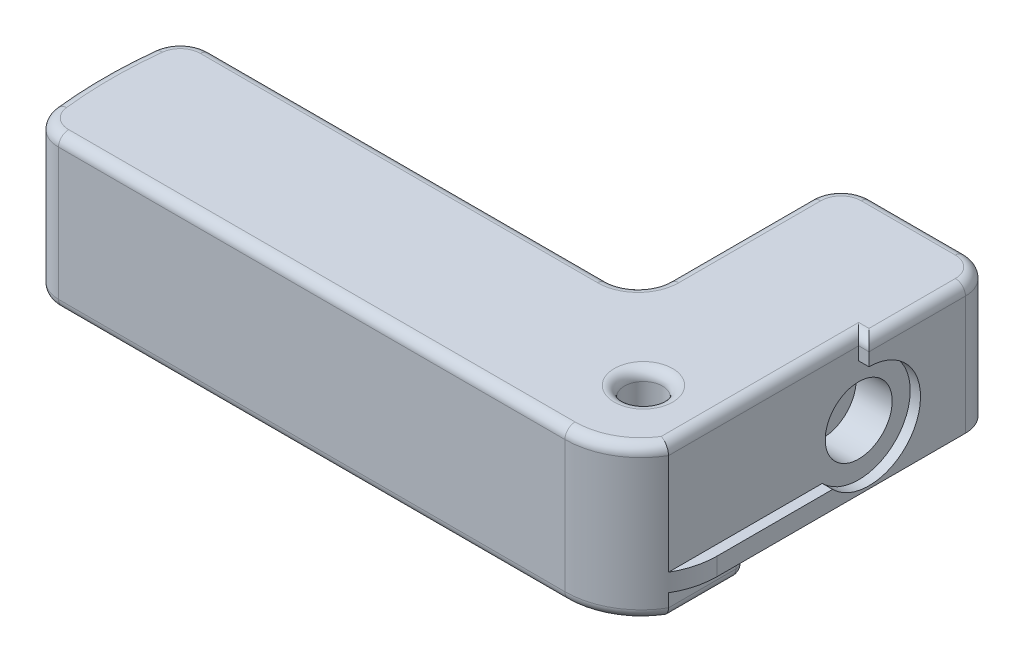
SolidWorks part; units mm, degrees
ref_plane "Front Plane" through (0, 0, 0) normal (0, 0, 1) x (1, 0, 0)
ref_plane "Top Plane" through (0, 0, 0) normal (0, 1, 0) x (1, 0, 0)
ref_plane "Right Plane" through (0, 0, 0) normal (1, 0, 0) x (0, 0, -1)
sketch "Sketch1" plane through (0, 0, 0) normal (0, 1, 0) x (1, 0, 0)
  line L0 (-60.8, 0) -> (0, 0)
  line L1 (0, 0) -> (0, 35)
  line L2 (0, 35) -> (-16.0369, 35)
  line L3 (-16.0369, 35) -> (-16.0369, 15)
  line L4 (-16.0369, 15) -> (-60.8, 15)
  line L6 (-16.0369, 15) -> (0, 0) construction
  circle A0 centre (-8.0184, 7.5) radius 1.875
  arc A1 (-60.8, 15) -> (-60.8, 0) centre (-18.0184, 7.5) ccw
  dimension "D3" = 3.75
  dimension "D5" = 60.8
  dimension "D6" = 43.434
  dimension "D1" = 35
  dimension "D2" = 15
  dimension "D4" = 16.0369
extrude "Boss-Extrude1" add sketch "Sketch1" along normal blind 15
sketch "Sketch2" plane through (0, 0, 0) normal (1, 0, 0) x (0, 0, -1)
  line L0 (22.486, 12.716) -> (22.486, 15)
  line L1 (35, 15) -> (35, 0) construction
  line L2 (0, 15) -> (35, 15) construction
  line L3 (5.625, 15) -> (9.375, 15) construction
  line L4 (0, 15) -> (0, 4.0439)
  line L5 (0, 4.0439) -> (18.8939, 4.0439)
  line L6 (22.486, 7.636) -> (18.8939, 4.0439) construction
  line L8 (0, 0) -> (35, 0) construction
  line L9 (0, 15) -> (0, 0) construction
  line L10 (0, 15) -> (22.486, 15)
  line L11 (0, 0) -> (35, 0)
  line L12 (0, 0) -> (0, 2.286)
  line L13 (0, 2.286) -> (35, 2.286)
  line L14 (35, 0) -> (35, 2.286)
  arc A0 (22.486, 12.716) -> (18.8939, 4.0439) centre (22.486, 7.636) cw
  point P3 (22.486, 2.556)
  point P22 (7.5, 15)
  dimension "D1" = 5.08
  dimension "D2" = 14.986
  dimension "D3" = 12.716
  dimension "D4" = 45
  dimension "D5" = 2.286
extrude "Cut-Extrude1" cut sketch "Sketch2" against normal blind 1.778
sketch "Sketch7" plane through (-1.778, 0, 0) normal (1, 0, 0) x (0, 0, -1)
  line L0 (0, 0) -> (35, 0) construction
  line L1 (11.375, 0) -> (35, 0)
  line L2 (11.375, 0) -> (11.375, 2.286)
  line L3 (11.375, 2.286) -> (35, 2.286)
  line L4 (35, 0) -> (35, 2.286)
  line L6 (9.375, 0) -> (9.375, 15) construction
  dimension "D1" = 2
extrude "Cut-Extrude6" cut sketch "Sketch7" against normal blind 5
sketch "Sketch3" plane through (-1.778, 0, 0) normal (1, 0, 0) x (0, 0, -1)
  circle A0 centre (22.486, 7.636) radius 3.302
  dimension "D1" = 6.604
extrude "Cut-Extrude2" cut sketch "Sketch3" against normal blind 3.556
sketch "Sketch4" plane through (0, 0, -15) normal (0, 0, -1) x (-1, 0, 0)
  line L0 (43.5784, 15) -> (43.5784, 0) construction
  line L1 (16.0369, 15) -> (60.8, 15) construction
  line L2 (16.0369, 0) -> (60.8, 0) construction
  line L4 (6.1434, 15) -> (9.8934, 15) construction
  circle A0 centre (43.5784, 7.5) radius 3.302
  point P12 (8.0184, 15)
  dimension "D1" = 6.604
  dimension "D2" = 35.56
extrude "Cut-Extrude3" cut sketch "Sketch4" against normal blind 3.302
sketch "Sketch5" plane through (0, 0, 0) normal (1, 0, 0) x (0, 0, -1)
  line L1 (35, 0) -> (0, 0)
  line L2 (35, 0) -> (35, 15)
  line L3 (35, 15) -> (0, 15)
  line L4 (0, 0) -> (0, 15)
extrude "Cut-Extrude4" cut sketch "Sketch5" against normal blind 0.762
sketch "Sketch6" plane through (0, 15, 0) normal (0, 1, 0) x (1, 0, 0)
  line L0 (-0.762, 18.8939) -> (-0.762, 0) construction
  line L1 (-60.8, 0) -> (-1.778, 0) construction
  line L2 (-8.262, 0) -> (-0.762, 0)
  line L3 (-0.762, 0) -> (-0.762, 7.5)
  arc A0 (-0.762, 7.5) -> (-8.262, 0) centre (-8.262, 7.5) cw
  dimension "D1" = 7.5
extrude "Cut-Extrude5" cut sketch "Sketch6" against normal through all
fillet "Fillet1" radius 3 5 edges at (-16.0369, 7.5, -15) (-0.762, 8.643, -35) (-16.0369, 7.5, -35) (-60.8, 7.5, 0) (-60.8, 7.5, -15)
fillet "Fillet2" radius 1 30 edges at (-8.0184, 0, -5.625) (-15.1582, 0, -34.1213) (-16.0369, 0, -25) (-16.9155, 0, -15.8787) (-38.6191, 0, -15) (-33.2316, 0, 0) (-4.5217, 0, -0.9992) (-1.778, 0, -7.5528) (-9.9074, 0, -35) (-1.27, 15, -22.486) (-1.778, 15, -13.1083) (-4.5217, 15, -0.9992) (-33.2316, 15, 0) (-38.6191, 15, -15) (-16.9155, 15, -15.8787) (-16.0369, 15, -25) (-15.1582, 15, -34.1213) (-8.3994, 15, -35) (-1.6407, 15, -34.1213) (-0.762, 15, -27.243) (-8.0184, 15, -5.625) (-4.278, 0, -11.375) (-6.778, 0, -23.1875) (-1.778, 1.143, -11.375) (-61.4524, 0, -7.5) (-61.4524, 15, -7.5) (-60.201, 0, -0.7637) (-60.201, 15, -0.7637) (-60.201, 0, -14.2363) (-60.201, 15, -14.2363)
